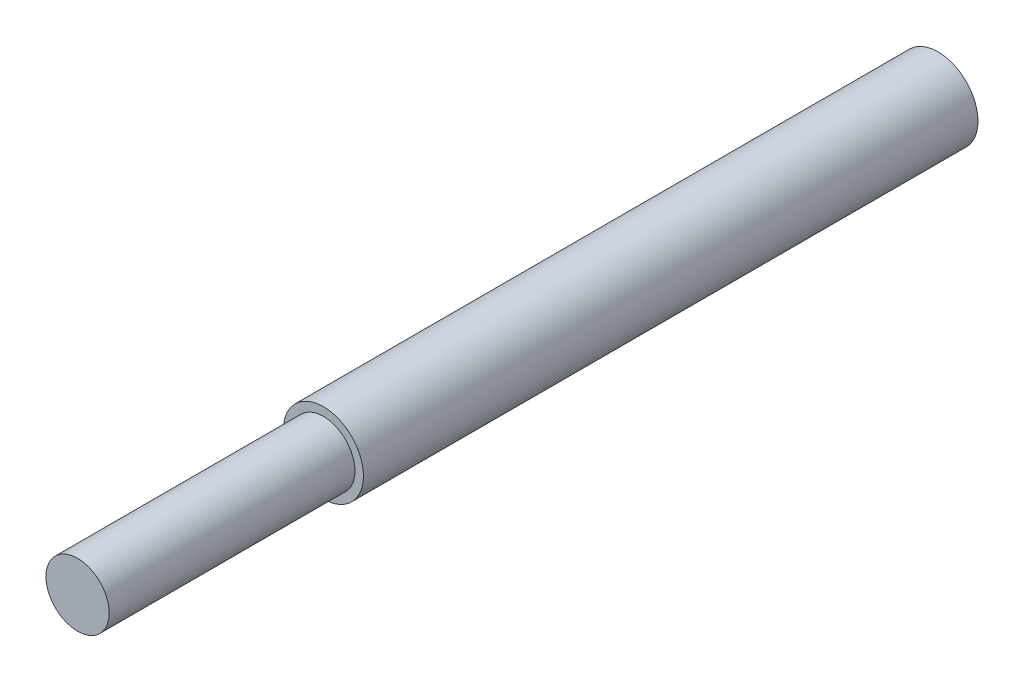
SolidWorks part; units mm, degrees
ref_plane "Front Plane" through (0, 0, 0) normal (0, 0, 1) x (1, 0, 0)
ref_plane "Top Plane" through (0, 0, 0) normal (0, 1, 0) x (1, 0, 0)
ref_plane "Right Plane" through (0, 0, 0) normal (1, 0, 0) x (0, 0, -1)
sketch "Sketch1" plane through (0, 0, 0) normal (0, 1, 0) x (1, 0, 0)
  line L0 (1.14, 0) -> (0, 0)
  line L1 (0, 0) -> (0, -17.5)
  line L2 (0, -17.5) -> (1.14, -17.5)
  line L3 (1.14, -17.5) -> (1.14, 0)
  line L4 (0, 0) -> (0, -17.5) construction
  dimension "D1" = 1.14
revolve "Revolve1" add sketch "Sketch1" angle 360 about L4
sketch "Sketch2" plane through (0, 0, 17.5) normal (0, 0, 1) x (1, 0, 0)
  circle A0 centre (0, 0) radius 0.9
  dimension "D1" = 1.8
extrude "Boss-Extrude1" add sketch "Sketch2" along normal blind 7
equation "\"D1@Boss-Extrude1\"=1.75mm*4"
